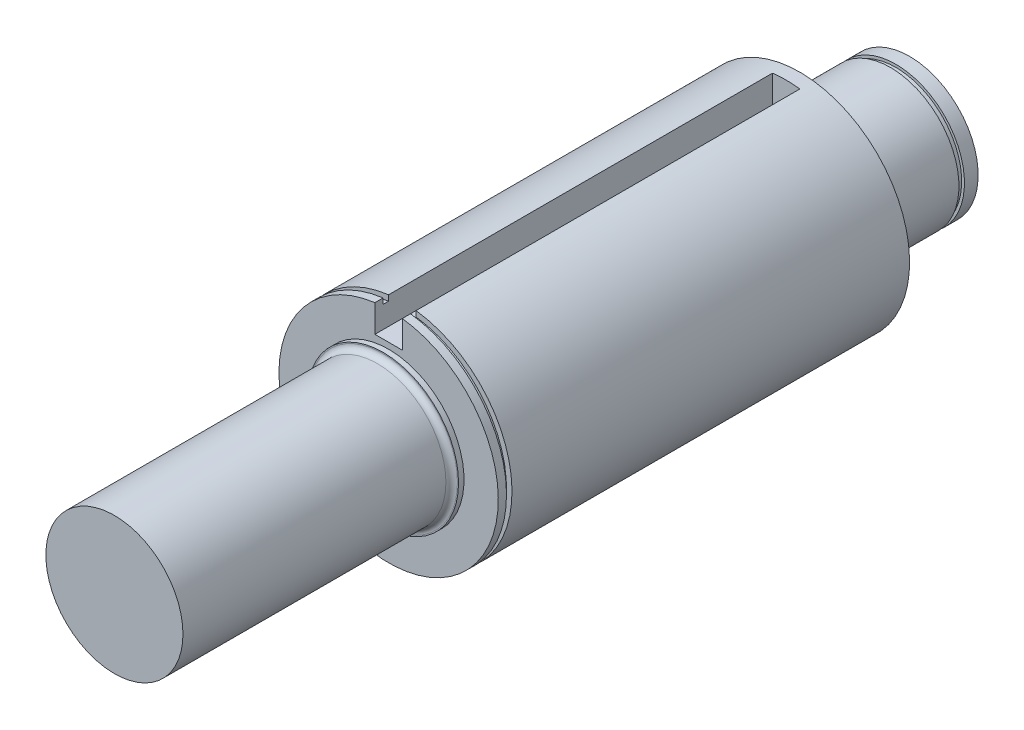
SolidWorks part; units mm, degrees
ref_plane "Plan de face" through (0, 0, 0) normal (0, 0, 1) x (1, 0, 0)
ref_plane "Plan de dessus" through (0, 0, 0) normal (0, 1, 0) x (1, 0, 0)
ref_plane "Plan de droite" through (0, 0, 0) normal (1, 0, 0) x (0, 0, -1)
sketch "Esquisse1" plane through (0, 0, 0) normal (0, 0, 1) x (1, 0, 0)
  circle A0 centre (0, 0) radius 25
  dimension "D1" = 50
extrude "Boss.-Extru.1" add sketch "Esquisse1" against normal blind 100
sketch "Esquisse4" plane through (0, 0, -100) normal (0, 0, -1) x (-1, 0, 0)
  line L0 (0, -1000) -> (0, 29.6863) construction
  line L2 (-5, -957.1075) -> (-5, 49042.8925) construction
  line L3 (5, -954.8323) -> (5, 49045.1677) construction
  line L4 (-5, 39.6863) -> (-5, 29.6863)
  line L5 (-5, 29.6863) -> (5, 29.6863)
  line L6 (5, 29.6863) -> (5, 39.6863)
  arc A0 (-5, 39.6863) -> (5, 39.6863) centre (0, 0) ccw
  point P10 (-5, 39.6863)
  point P12 (5, 39.6863)
  dimension "D1" = 80
  dimension "D3" = 5
  dimension "D4" = 5
  dimension "D5" = 10
extrude "Boss.-Extru.3" add sketch "Esquisse4" along normal blind 150
sketch "Esquisse5" plane through (0, 0, -250) normal (0, 0, -1) x (-1, 0, 0)
  circle A0 centre (0, 0) radius 25
  dimension "D1" = 50
extrude "Boss.-Extru.4" add sketch "Esquisse5" along normal blind 40
sketch "Esquisse6" plane through (0, 0, -100) normal (0, 0, 1) x (1, 0, 0)
  circle A0 centre (0, 0) radius 27.5
  dimension "D1" = 55
extrude "Boss.-Extru.5" add sketch "Esquisse6" along normal blind 2
fillet "Congé2" radius 2.1 1 edges at (25, 0, -98)
ref_plane "Plan1" through (0, 0, -175) normal (0, 0, 1) x (1, 0, 0)
mirror "Symétrie3" about plane through (0, 0, -175) normal (0, 0, 1) of "Boss.-Extru.5"
fillet "Congé3" radius 2.1 1 edges at (-25, 0, -252)
ref_plane "Plan2" through (0, 0, -283) normal (0, 0, -1) x (-1, 0, 0)
sketch "Esquisse7" plane through (0, 0, -283) normal (0, 0, -1) x (-1, 0, 0)
  circle A0 centre (0, 0) radius 25
  circle A1 centre (0, 0) radius 24
  dimension "D1" = 50
  dimension "D2" = 48
extrude "Enlèv. mat.-Extru.1" cut sketch "Esquisse7" along normal blind 2
sketch "Esquisse9" plane through (0, 0, -250) normal (0, 0, -1) x (-1, 0, 0)
  line L0 (-5, 39.6863) -> (-5, 29.6863)
  line L1 (-5, 29.6863) -> (5, 29.6863)
  line L2 (5, 29.6863) -> (5, 39.6863)
  arc A0 (-5, 39.6863) -> (5, 39.6863) centre (0, 0) cw
  arc A1 (-5, 39.6863) -> (5, 39.6863) centre (0, 0) ccw construction
  line M3 (5, 39.6863) -> (5, 29.6863)
  line M4 (5, 29.6863) -> (-5, 29.6863)
  line M5 (-5, 29.6863) -> (-5, 39.6863)
extrude "Boss.-Extru.6" add sketch "Esquisse9" against normal blind 5 contours A0 M5 M4 M3
ref_plane "Plan3" through (0, 0, -105) normal (0, 0, 1) x (1, 0, 0)
sketch "Esquisse10" plane through (0, 0, -105) normal (0, 0, 1) x (1, 0, 0)
  circle A0 centre (0, 0) radius 40
  circle A1 centre (0, 0) radius 38
  dimension "D1" = 76
extrude "Enlèv. mat.-Extru.2" cut sketch "Esquisse10" along normal blind 2
